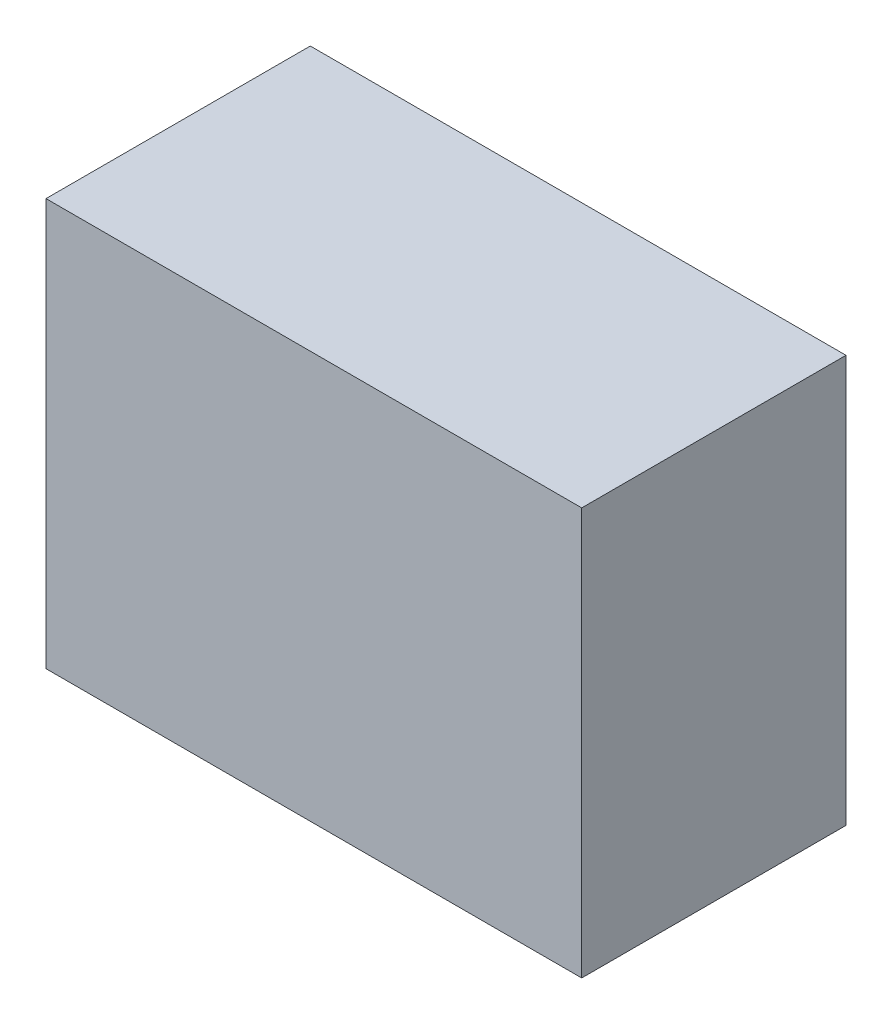
SolidWorks part; units mm, degrees
ref_plane "정면" through (0, 0, 0) normal (0, 0, 1) x (1, 0, 0)
ref_plane "윗면" through (0, 0, 0) normal (0, 1, 0) x (1, 0, 0)
ref_plane "우측면" through (0, 0, 0) normal (1, 0, 0) x (0, 0, -1)
sketch "스케치1" plane through (0, 0, 0) normal (0, 0, 1) x (1, 0, 0)
  line L1 (0, 0) -> (75, 0)
  line L2 (0, 0) -> (0, 57)
  line L3 (0, 57) -> (75, 57)
  line L4 (75, 0) -> (75, 57)
  dimension "D1" = 57
  dimension "D2" = 75
extrude "보스-돌출1" add sketch "스케치1" along normal blind 37
